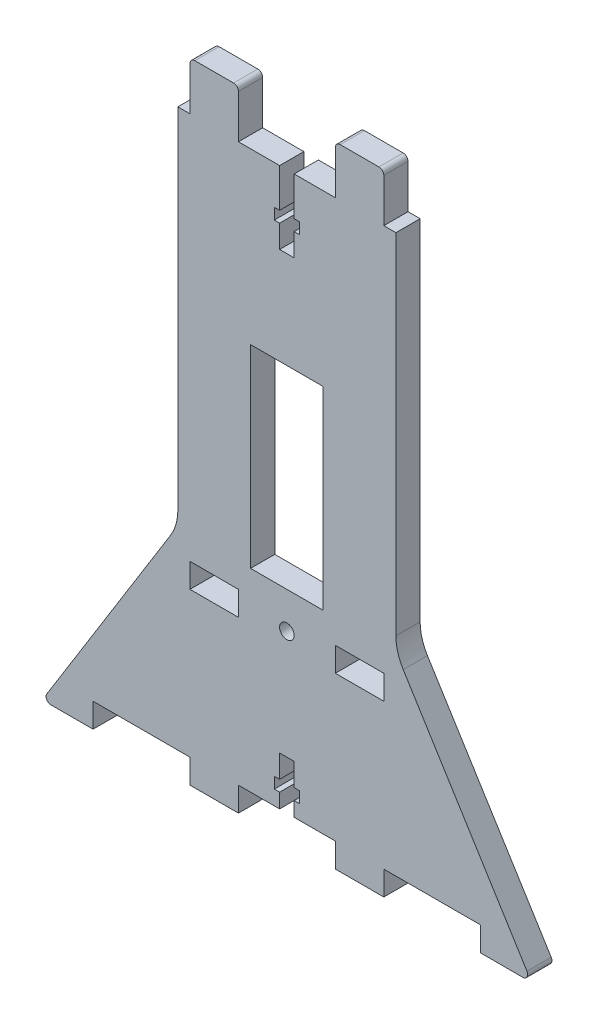
SolidWorks part; units mm, degrees
ref_plane "Front Plane" through (0, 0, 0) normal (0, 0, 1) x (1, 0, 0)
ref_plane "Top Plane" through (0, 0, 0) normal (0, 1, 0) x (1, 0, 0)
ref_plane "Right Plane" through (0, 0, 0) normal (1, 0, 0) x (0, 0, -1)
sketch "Sketch1" plane through (0, 0, 0) normal (0, 0, 1) x (1, 0, 0)
  line L1 (-50.0189, -56.1915) -> (-30.0189, -56.1915)
  line L2 (-30.0189, -56.1915) -> (-30.0189, -61.1915)
  line L3 (-30.0189, -61.1915) -> (-20.0189, -61.1915)
  line L4 (-20.0189, -61.1915) -> (-20.0189, -56.1915)
  line L6 (-0.0189, -56.1915) -> (-0.0189, -61.1915)
  line L7 (-0.0189, -61.1915) -> (9.9811, -61.1915)
  line L8 (9.9811, -61.1915) -> (9.9811, -56.1915)
  line L9 (9.9811, -56.1915) -> (29.9811, -56.1915)
  line L12 (-38.5749, -16.1038) -> (31.2699, -16.1038) construction
  line L13 (-11.5189, -56.1915) -> (-8.5189, -56.1915) construction
  line L14 (-8.5189, -56.1915) -> (-8.5189, -53.1915)
  line L15 (-8.5189, -50.8915) -> (-7.4189, -50.8915)
  line L16 (-12.6189, -53.1915) -> (-12.6189, -50.8915)
  line L17 (-7.4189, -53.1915) -> (-8.5189, -53.1915)
  line L18 (-8.5189, -50.8915) -> (-8.5189, -46.1915)
  line L19 (-8.5189, -46.1915) -> (-11.5189, -46.1915)
  line L20 (-11.5189, -46.1915) -> (-11.5189, -50.8915)
  line L21 (-11.5189, -53.1915) -> (-12.6189, -53.1915)
  line L22 (-7.4189, -50.8915) -> (-7.4189, -53.1915)
  line L23 (-12.6189, -50.8915) -> (-11.5189, -50.8915)
  line L24 (-11.5189, -53.1915) -> (-11.5189, -56.1915)
  line L25 (-10.0189, -46.1915) -> (-10.0189, -56.1915) construction
  line L26 (-11.5189, -56.1915) -> (-20.0189, -56.1915)
  line L27 (-8.5189, -56.1915) -> (-0.0189, -56.1915)
  line L28 (-10.0189, 43.8085) -> (-10.0189, 53.8085) construction
  line L29 (-11.5189, 58.8085) -> (-8.5189, 58.8085) construction
  line L30 (-10.0189, -57.0002) -> (-10.0189, 91.0448) construction
  line L31 (-8.5189, 58.8085) -> (-0.0189, 58.8085)
  line L32 (-11.5189, 58.8085) -> (-20.0189, 58.8085)
  line L33 (-11.5189, 50.8085) -> (-11.5189, 58.8085)
  line L34 (-12.6189, 48.5085) -> (-11.5189, 48.5085)
  line L35 (-7.4189, 48.5085) -> (-7.4189, 50.8085)
  line L36 (-11.5189, 50.8085) -> (-12.6189, 50.8085)
  line L37 (-11.5189, 43.8085) -> (-11.5189, 48.5085)
  line L38 (-8.5189, 43.8085) -> (-11.5189, 43.8085)
  line L39 (-8.5189, 48.5085) -> (-8.5189, 43.8085)
  line L40 (-7.4189, 50.8085) -> (-8.5189, 50.8085)
  line L41 (-12.6189, 50.8085) -> (-12.6189, 48.5085)
  line L42 (-8.5189, 48.5085) -> (-7.4189, 48.5085)
  line L43 (-8.5189, 58.8085) -> (-8.5189, 50.8085)
  line L44 (9.9811, 58.8085) -> (12.4811, 58.8085)
  line L45 (9.9811, 68.8085) -> (9.9811, 58.8085)
  line L46 (-0.0189, 68.8085) -> (9.9811, 68.8085)
  line L47 (-0.0189, 58.8085) -> (-0.0189, 68.8085)
  line L48 (-20.0189, 68.8085) -> (-20.0189, 58.8085)
  line L49 (-30.0189, 68.8085) -> (-20.0189, 68.8085)
  line L50 (-30.0189, 58.8085) -> (-30.0189, 68.8085)
  line L51 (-32.5189, 58.8085) -> (-30.0189, 58.8085)
  line L52 (-50.0189, -56.1915) -> (-50.0189, -61.1915)
  line L53 (-50.0189, -61.1915) -> (-60.5189, -61.1915)
  line L54 (-60.5189, -61.1915) -> (-32.5189, -16.1038)
  line L55 (-32.5189, 58.8085) -> (-32.5189, -16.1038)
  line L56 (29.9811, -56.1915) -> (29.9811, -61.1915)
  line L57 (29.9811, -61.1915) -> (40.4811, -61.1915)
  line L58 (40.4811, -61.1915) -> (12.4811, -16.1038)
  line L59 (12.4811, -16.1038) -> (12.4811, 58.8085)
  point P2 (-0.0189, -58.6915)
  point P57 (-10.0189, 43.8085)
  dimension "D1" = 10
  dimension "D2" = 10
  dimension "D3" = 5
  dimension "D4" = 20
  dimension "D5" = 101
  dimension "D6" = 20
  dimension "D7" = 5.2
  dimension "D8" = 3
  dimension "D9" = 2.3
  dimension "D10" = 3
  dimension "D11" = 10
  dimension "D12" = 5
  dimension "D13" = 50.5
  dimension "D14" = 20
  dimension "D15" = 3
  dimension "D16" = 3
  dimension "D17" = 5.2
  dimension "D18" = 45
  dimension "D19" = 10
  dimension "D20" = 20
  dimension "D21" = 22.5
  dimension "D22" = 2.5
  dimension "D24" = 10
  dimension "D25" = 5
  dimension "D26" = 2.5
  dimension "D27" = 10
  dimension "D28" = 53.0745
extrude "Boss-Extrude1" add sketch "Sketch1" along normal blind 5
sketch "Sketch2" plane through (0, 0, 5) normal (0, 0, 1) x (1, 0, 0)
  line L0 (-37.0155, -21.1915) -> (22.4174, -21.1915) construction
  line L2 (-30.0189, -21.1915) -> (-20.0189, -21.1915)
  line L3 (-30.0189, -21.1915) -> (-30.0189, -26.1915)
  line L4 (-30.0189, -26.1915) -> (-20.0189, -26.1915)
  line L5 (-20.0189, -21.1915) -> (-20.0189, -26.1915)
  line L6 (-0.0189, -21.1915) -> (9.9811, -21.1915)
  line L7 (-0.0189, -21.1915) -> (-0.0189, -26.1915)
  line L8 (-0.0189, -26.1915) -> (9.9811, -26.1915)
  line L9 (9.9811, -21.1915) -> (9.9811, -26.1915)
  line L10 (-2.5189, 23.8085) -> (-17.5189, 23.8085)
  line L11 (-2.5189, 23.8085) -> (-2.5189, -16.1915)
  line L12 (-2.5189, -16.1915) -> (-17.5189, -16.1915)
  line L13 (-17.5189, 23.8085) -> (-17.5189, -16.1915)
  line L14 (-30.0189, 58.8085) -> (-32.5189, 58.8085) construction
  line L15 (-35.7615, -23.6915) -> (19.4664, -23.6915) construction
  line L16 (-10.0189, 50.0273) -> (-10.0189, 1.4719) construction
  line L17 (-8.5189, 43.8085) -> (-11.5189, 43.8085) construction
  line L21 (-32.5189, 58.8085) -> (-32.5189, -16.1038) construction
  line L22 (12.4811, -16.1038) -> (12.4811, 58.8085) construction
  circle A0 centre (-10.0189, -23.6915) radius 1.5
  point P22 (9.9811, -23.6915)
  point P29 (-10.0189, 43.8085)
  dimension "D2" = 5
  dimension "D3" = 10
  dimension "D1" = 80
  dimension "D4" = 10
  dimension "D5" = 10
  dimension "D6" = 10
  dimension "D7" = 2.5
  dimension "D8" = 2.5
  dimension "D9" = 40
  dimension "D10" = 15
  dimension "D11" = 5
extrude "Cut-Extrude1" cut sketch "Sketch2" against normal blind 10
ref_plane "Plane4" through (12.4811, 58.8085, 5) normal (0, 1, 0) x (1, 0, 0)
fillet "Fillet1" radius 10 2 edges at (12.4811, -16.1038, 2.5) (-32.5189, -16.1038, 2.5)
fillet "Fillet2" radius 1 2 edges at (-60.5189, -61.1915, 2.5) (40.4811, -61.1915, 2.5)
fillet "Congé1" radius 1 4 edges at (-30.0189, 68.8085, 2.5) (-20.0189, 68.8085, 2.5) (-0.0189, 68.8085, 2.5) (9.9811, 68.8085, 2.5)
